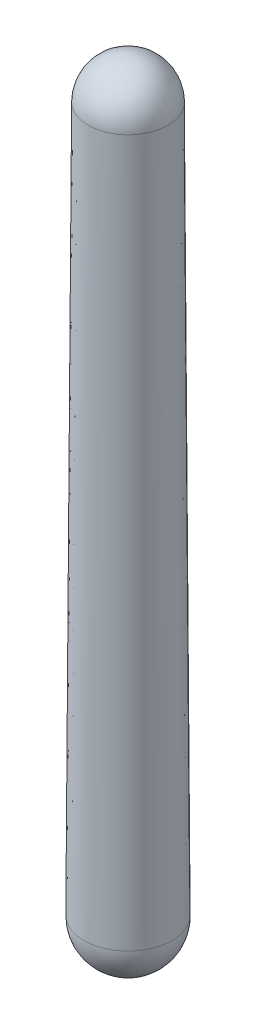
SolidWorks part; units mm, degrees
material "Nylon 101"
ref_plane "Alzado" through (0, 0, 0) normal (0, 0, 1) x (1, 0, 0)
ref_plane "Planta" through (0, 0, 0) normal (0, 1, 0) x (1, 0, 0)
ref_plane "Vista lateral" through (0, 0, 0) normal (1, 0, 0) x (0, 0, -1)
sketch "Sketch1" plane through (0, 0, 0) normal (0, 0, 1) x (1, 0, 0)
  line L0 (0, 0) -> (6.8, 0)
  line L1 (6.8, 0) -> (7.5, -120)
  line L2 (7.5, -120) -> (0, -120)
  line L3 (0, -120) -> (0, 0)
  line L4 (0, -124) -> (0, 4) construction
revolve "Diafisis" add sketch "Sketch1" angle 360 about L4
sketch "Sketch2" plane through (0, 0, 0) normal (0, 0, 1) x (1, 0, 0)
  line L0 (0, -6.8) -> (0, 6.8)
  line L1 (0, -10.8) -> (0, 10.8) construction
  arc A0 (0, 6.8) -> (0, -6.8) centre (0, 0) cw
revolve "Union_proximal" add sketch "Sketch2" angle 360 about L1
sketch "Sketch3" plane through (0, 0, 0) normal (0, 0, 1) x (1, 0, 0)
  line L0 (0, -127.5) -> (0, -112.5)
  line L1 (0, -131.5) -> (0, -108.5) construction
  arc A0 (0, -112.5) -> (0, -127.5) centre (0, -120) cw
revolve "Union_distal" add sketch "Sketch3" angle 360 about L1
